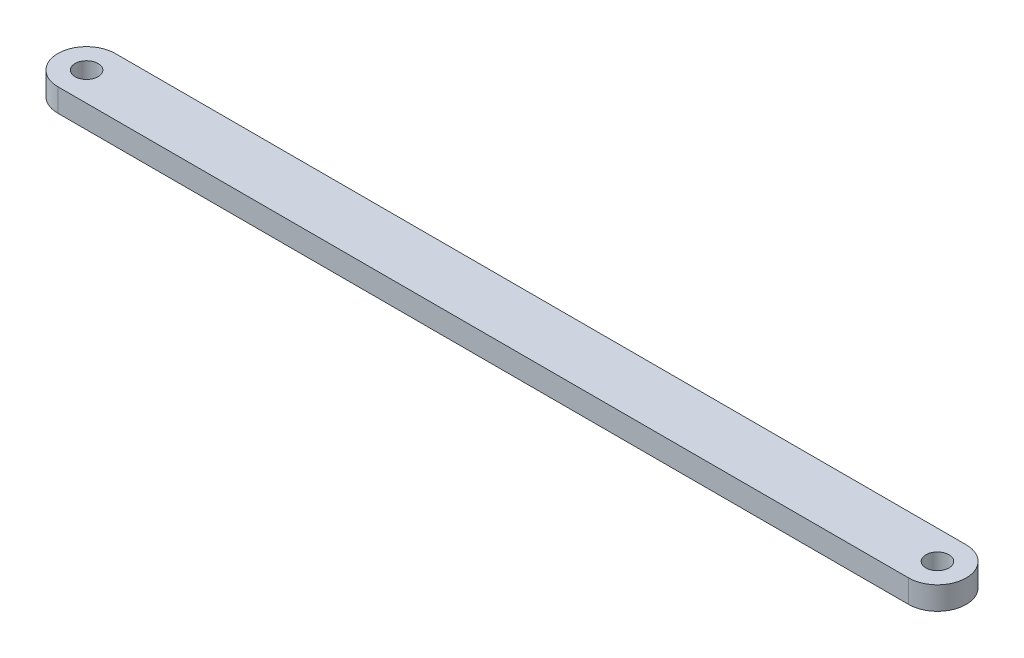
SolidWorks part; units mm, degrees
ref_plane "Front Plane" through (0, 0, 0) normal (0, 0, 1) x (1, 0, 0)
ref_plane "Top Plane" through (0, 0, 0) normal (0, 1, 0) x (1, 0, 0)
ref_plane "Right Plane" through (0, 0, 0) normal (1, 0, 0) x (0, 0, -1)
sketch "Sketch1" plane through (0, 0, 0) normal (0, 1, 0) x (1, 0, 0)
  line L0 (0, 0) -> (-74, 0)
  line L1 (-74, 0) -> (-74, -5) construction
  line L2 (-74, -5) -> (0, -5)
  line L3 (0, -5) -> (0, 0) construction
  arc A0 (0, 0) -> (0, -5) centre (0, -2.5) cw
  arc A1 (-74, 0) -> (-74, -5) centre (-74, -2.5) ccw
  circle A2 centre (-74, -2.5) radius 1
  circle A3 centre (0, -2.5) radius 1
  dimension "D3" = 2
  dimension "D1" = 74
  dimension "D2" = 5
extrude "Boss-Extrude1" add sketch "Sketch1" along normal blind 2
